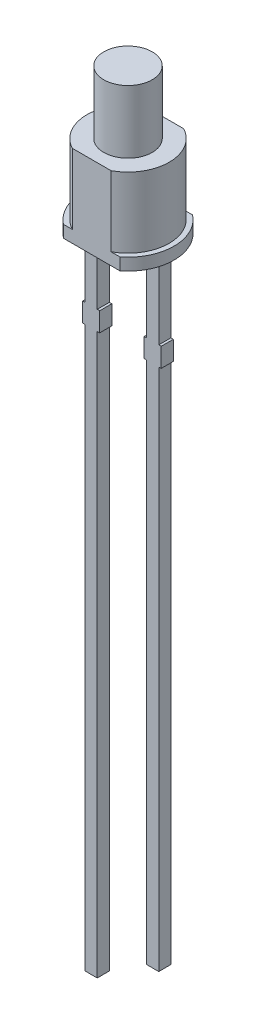
SolidWorks part; units mm, degrees
ref_plane "Спереди" through (0, 0, 0) normal (0, 0, 1) x (1, 0, 0)
ref_plane "Сверху" through (0, 0, 0) normal (0, 1, 0) x (1, 0, 0)
ref_plane "Справа" through (0, 0, 0) normal (1, 0, 0) x (0, 0, -1)
sketch "Эскиз1" plane through (0, 0, 0) normal (0, 1, 0) x (1, 0, 0)
  circle A0 centre (0, 0) radius 1.9
extrude "Бобышка-Вытянуть1" add sketch "Эскиз1" along normal blind 0.5 contours A0
sketch "Эскиз2" plane through (0, 0.5, 0) normal (0, 1, 0) x (1, 0, 0)
  circle A0 centre (0, 0) radius 1.7
extrude "Бобышка-Вытянуть2" add sketch "Эскиз2" along normal blind 2.9
sketch "Эскиз3" plane through (0, 3.4, 0) normal (0, 1, 0) x (1, 0, 0)
  circle A0 centre (0, 0) radius 1
extrude "Бобышка-Вытянуть3" add sketch "Эскиз3" along normal blind 2.6
sketch "Эскиз4" plane through (0, 0, 0) normal (0, 0, 1) x (1, 0, 0)
  line L0 (1.27, 0) -> (1.27, -27) construction
  line L1 (-1.9, 0) -> (1.9, 0) construction
  line L2 (0, 0) -> (0, -10.9573) construction
  line L3 (-1.27, -27) -> (-1.27, 0) construction
  line L5 (1.02, -25.5) -> (1.52, -25.5)
  line L6 (1.02, -25.5) -> (1.02, 0)
  line L7 (1.02, 0) -> (1.52, 0)
  line L8 (1.52, -25.5) -> (1.52, 0)
  line L9 (-1.02, -27) -> (-1.52, -27)
  line L10 (-1.02, -27) -> (-1.02, 0)
  line L11 (-1.02, 0) -> (-1.52, 0)
  line L12 (-1.52, -27) -> (-1.52, 0)
  line L13 (1.62, -3.8851) -> (0.92, -3.8851)
  line L14 (1.62, -3.8851) -> (1.62, -3.0937)
  line L15 (1.62, -3.0937) -> (0.92, -3.0937)
  line L16 (0.92, -3.8851) -> (0.92, -3.0937)
  line L17 (1.62, -3.8851) -> (0.92, -3.0937) construction
  line L18 (1.62, -3.0937) -> (0.92, -3.8851) construction
  line L19 (-0.92, -3.8851) -> (-1.62, -3.8851)
  line L20 (-0.92, -3.8851) -> (-0.92, -3.0937)
  line L21 (-0.92, -3.0937) -> (-1.62, -3.0937)
  line L22 (-1.62, -3.8851) -> (-1.62, -3.0937)
  line L23 (-0.92, -3.8851) -> (-1.62, -3.0937) construction
  line L24 (-0.92, -3.0937) -> (-1.62, -3.8851) construction
  point P16 (-1.27, 0)
  point P17 (1.27, 0)
  point P18 (1.27, -3.4894)
  point P23 (-1.27, -3.4894)
  point P28 (0, 0)
  point P29 (1.27, -3.4894)
  dimension "D1" = 2.54
  dimension "D2" = 0.5
  dimension "D3" = 0.7
  dimension "D4" = 1.5
  dimension "D5" = 27
extrude "Бобышка-Вытянуть4" add sketch "Эскиз4" along normal mid plane 0.5 contours L8 L13 L6 L5 | L15 L8 L7 L6 | L14 L15 L8 L13 | L16 L13 L6 L15 | L10 L19 L12 L9 | L21 L10 L11 L12 | L10 L21 L12 L19 | L20 L21 L10 L19 | L22 L19 L12 L21
sketch "Эскиз5" plane through (0, 0, 0) normal (0, -1, 0) x (1, 0, 0)
  line L1 (-2.6294, -1.5) -> (2.6294, -1.5)
  line L2 (-2.6294, -1.5) -> (-2.6294, 1.5)
  line L3 (-2.6294, 1.5) -> (2.6294, 1.5)
  line L4 (2.6294, -1.5) -> (2.6294, 1.5)
  line L5 (-2.6294, -1.5) -> (2.6294, 1.5) construction
  line L6 (-2.6294, 1.5) -> (2.6294, -1.5) construction
  line L7 (-3.4813, -2.8419) -> (3.4813, -2.8419)
  line L8 (-3.4813, -2.8419) -> (-3.4813, 2.8419)
  line L9 (-3.4813, 2.8419) -> (3.4813, 2.8419)
  line L10 (3.4813, -2.8419) -> (3.4813, 2.8419)
  line L11 (-3.4813, -2.8419) -> (3.4813, 2.8419) construction
  line L12 (-3.4813, 2.8419) -> (3.4813, -2.8419) construction
  point P0 (0, 0)
  point P6 (0, 0)
  dimension "D1" = 3
extrude "Вырез-Вытянуть2" cut sketch "Эскиз5" against normal up to surface (6 mm away) up to face at (0, 6, 1)
